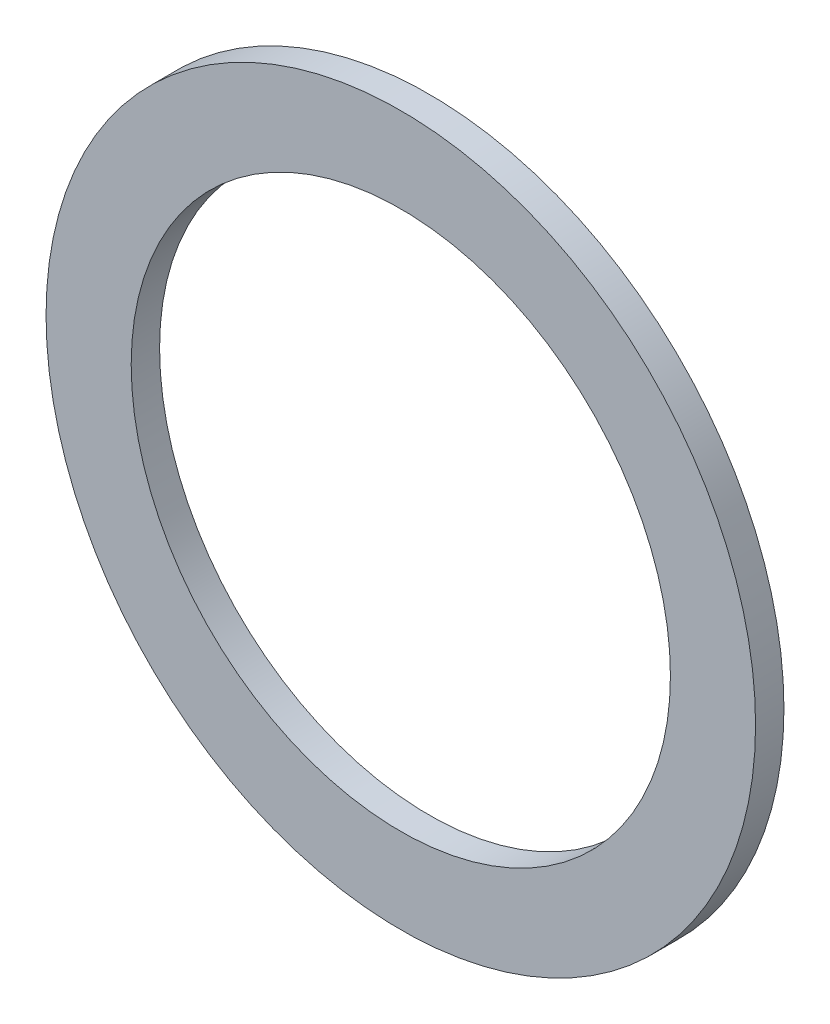
SolidWorks part; units mm, degrees
ref_plane "Ebene vorne" through (0, 0, 0) normal (0, 0, 1) x (1, 0, 0)
ref_plane "Ebene oben" through (0, 0, 0) normal (0, 1, 0) x (1, 0, 0)
ref_plane "Ebene rechts" through (0, 0, 0) normal (1, 0, 0) x (0, 0, -1)
sketch "Skizze1" plane through (0, 0, 0) normal (0, 0, 1) x (1, 0, 0)
  circle A0 centre (0, 0) radius 25
  dimension "D1" = 50
extrude "Aufsatz-Linear austragen1" add sketch "Skizze1" along normal blind 2
sketch "Skizze2" plane through (0, 0, 2) normal (0, 0, 1) x (1, 0, 0)
  circle A0 centre (0, 0) radius 19
  dimension "D1" = 38
extrude "Schnitt-Linear austragen1" cut sketch "Skizze2" against normal through all
